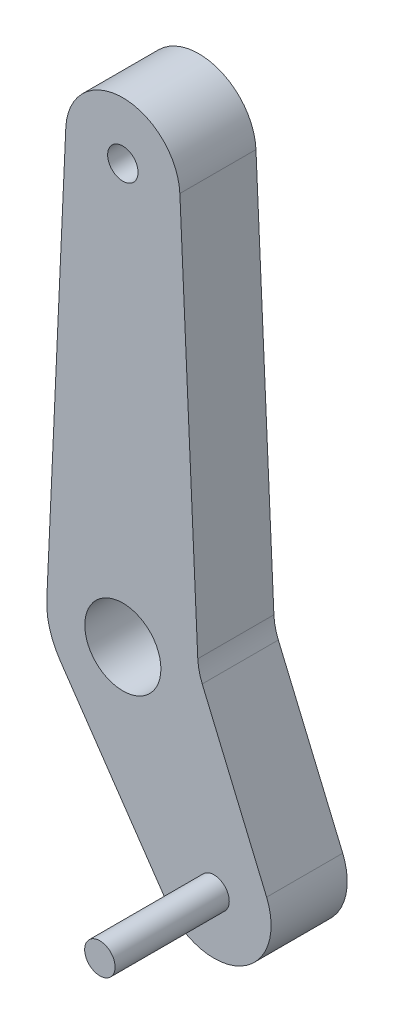
SolidWorks part; units mm, degrees
ref_plane "前视基准面" through (0, 0, 0) normal (0, 0, 1) x (1, 0, 0)
ref_plane "上视基准面" through (0, 0, 0) normal (0, 1, 0) x (1, 0, 0)
ref_plane "右视基准面" through (0, 0, 0) normal (1, 0, 0) x (0, 0, -1)
other "Configuration Table"
sketch "草图1" plane through (0, 0, 0) normal (0, 0, 1) x (1, 0, 0)
  line L0 (-14.9845, 110.6818) -> (-19.9793, 0.9091)
  line L1 (14.9845, 110.6818) -> (19.6946, 7.1672)
  line L2 (0, 0) -> (23.9652, -43.8824) construction
  line L3 (-16.5064, -11.2933) -> (11.5855, -52.3524)
  line L4 (37.7829, -38.0454) -> (20.8614, 2.0119)
  arc A3 (-19.9793, 0.9091) -> (-16.5064, -11.2933) centre (0, 0) ccw
  circle A6 centre (0, 0) radius 10
  arc A7 (14.9845, 110.6818) -> (-14.9845, 110.6818) centre (0, 110) ccw
  arc A8 (11.5855, -52.3524) -> (37.7829, -38.0454) centre (23.9652, -43.8824) ccw
  circle A9 centre (0, 110) radius 4
  arc A10 (19.6946, 7.1672) -> (20.8614, 2.0119) centre (34.6791, 7.849) ccw
  dimension "D1" = 15
extrude "凸台-拉伸1" add sketch "草图1" along normal blind 20
sketch "草图2" plane through (0, 0, 20) normal (0, 0, 1) x (1, 0, 0)
  circle A0 centre (23.9652, -43.8824) radius 4
extrude "凸台-拉伸2" add sketch "草图2" along normal blind 30
